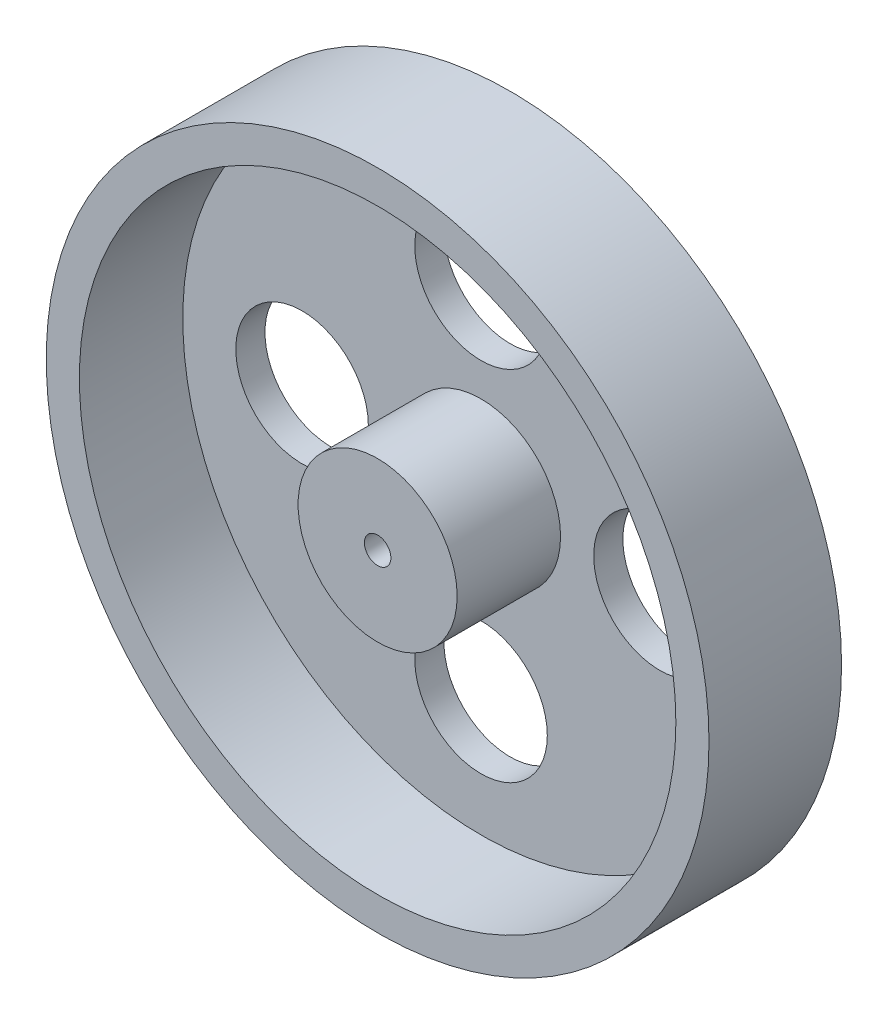
SolidWorks part; units mm, degrees
ref_plane "Front Plane" through (0, 0, 0) normal (0, 0, 1) x (1, 0, 0)
ref_plane "Top Plane" through (0, 0, 0) normal (0, 1, 0) x (1, 0, 0)
ref_plane "Right Plane" through (0, 0, 0) normal (1, 0, 0) x (0, 0, -1)
sketch "Sketch1" plane through (0, 0, 0) normal (0, 0, 1) x (1, 0, 0)
  circle A0 centre (0, 0) radius 25
extrude "Wheel_Web_50mm" add sketch "Sketch1" along normal blind 2.2 from offset 0
sketch "Sketch2" plane through (0, 0, 0) normal (0, 0, 1) x (1, 0, 0)
  circle A0 centre (0, 0) radius 25
  circle A1 centre (0, 0) radius 22.5
extrude "Outer_Rim_10mm_Wide" add sketch "Sketch2" along normal blind 7.8 from offset 2.2
sketch "Sketch3" plane through (0, 0, 0) normal (0, 0, 1) x (1, 0, 0)
  circle A0 centre (0, 0) radius 6
extrude "Hub_12mm" add sketch "Sketch3" along normal blind 7.8 from offset 2.2
sketch "Sketch4" plane through (0, 0, 0) normal (0, 0, 1) x (1, 0, 0)
  circle A0 centre (0, 0) radius 1
extrude "Axle_Bore_FIT_CHECK" cut sketch "Sketch4" along normal blind 10.2 from offset 0.1
sketch "Sketch5" plane through (0, 0, 0) normal (0, 0, 1) x (1, 0, 0)
  circle A0 centre (-13.5, 0) radius 5
extrude "Lightening_X_-13.5" cut sketch "Sketch5" along normal blind 10.2 from offset 0.1
sketch "Sketch6" plane through (0, 0, 0) normal (0, 0, 1) x (1, 0, 0)
  circle A0 centre (13.5, 0) radius 5
extrude "Lightening_X_13.5" cut sketch "Sketch6" along normal blind 10.2 from offset 0.1
sketch "Sketch7" plane through (0, 0, 0) normal (0, 0, 1) x (1, 0, 0)
  circle A0 centre (0, -13.5) radius 5
extrude "Lightening_Y_-13.5" cut sketch "Sketch7" along normal blind 10.2 from offset 0.1
sketch "Sketch8" plane through (0, 0, 0) normal (0, 0, 1) x (1, 0, 0)
  circle A0 centre (0, 13.5) radius 5
extrude "Lightening_Y_13.5" cut sketch "Sketch8" along normal blind 10.2 from offset 0.1
